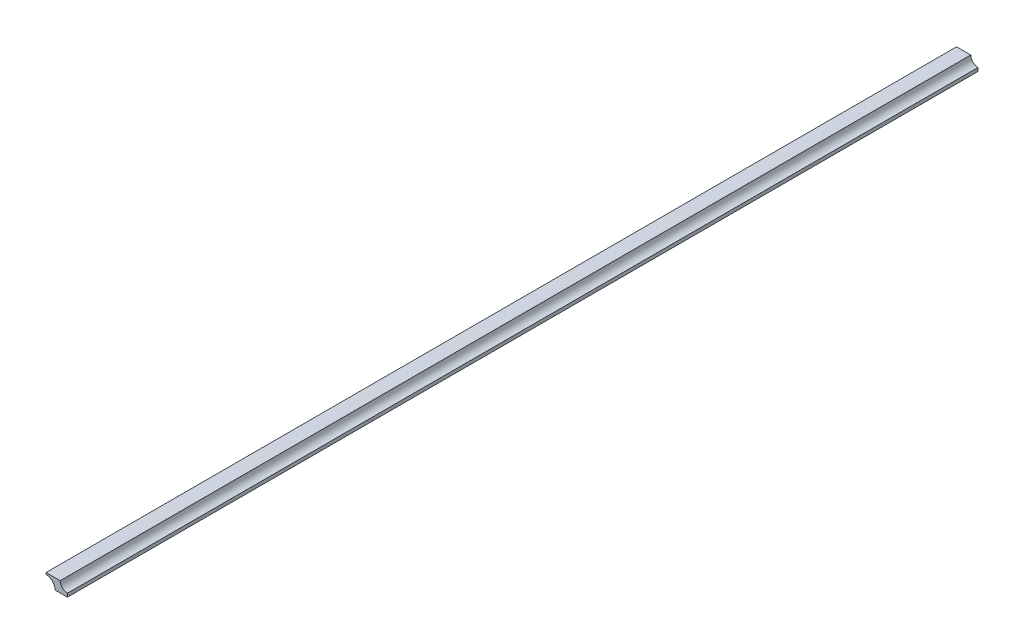
SolidWorks part; units mm, degrees
ref_plane "Front Plane" through (0, 0, 0) normal (0, 0, 1) x (1, 0, 0)
ref_plane "Top Plane" through (0, 0, 0) normal (0, 1, 0) x (1, 0, 0)
ref_plane "Right Plane" through (0, 0, 0) normal (1, 0, 0) x (0, 0, -1)
sketch "Sketch1" plane through (0, 0, 0) normal (0, 0, 1) x (1, 0, 0)
  line L1 (7.94, 0) -> (18.8, 0)
  line L2 (0, 7.94) -> (0, 9.4)
  line L3 (0, 9.4) -> (12.45, 9.4)
  line L4 (18.8, 0) -> (18.8, 3.05)
  arc A0 (7.94, 0) -> (0, 7.94) centre (0, 0) ccw
  arc A1 (12.45, 9.4) -> (18.8, 3.05) centre (18.8, 9.4) ccw
  dimension "D3" = 7.94
  dimension "D4" = 6.35
  dimension "D1" = 18.8
  dimension "D2" = 9.4
extrude "Boss-Extrude1" add sketch "Sketch1" along normal blind 800
equation "\"CoolantRadius\"= 7.94mm"
equation "\"FuelRadius\"= 6.35mm"
equation "\"D3@Sketch1\"=\"CoolantRadius\""
equation "\"D4@Sketch1\"=\"FuelRadius\""
equation "\"Length\" = 18.8mm"
equation "\"Width\"= 9.40mm"
equation "\"Height\"= 800mm"
equation "\"D1@Sketch1\"=\"Length\""
equation "\"D2@Sketch1\"=\"Width\""
equation "\"D1@Boss-Extrude1\"=\"Height\""
